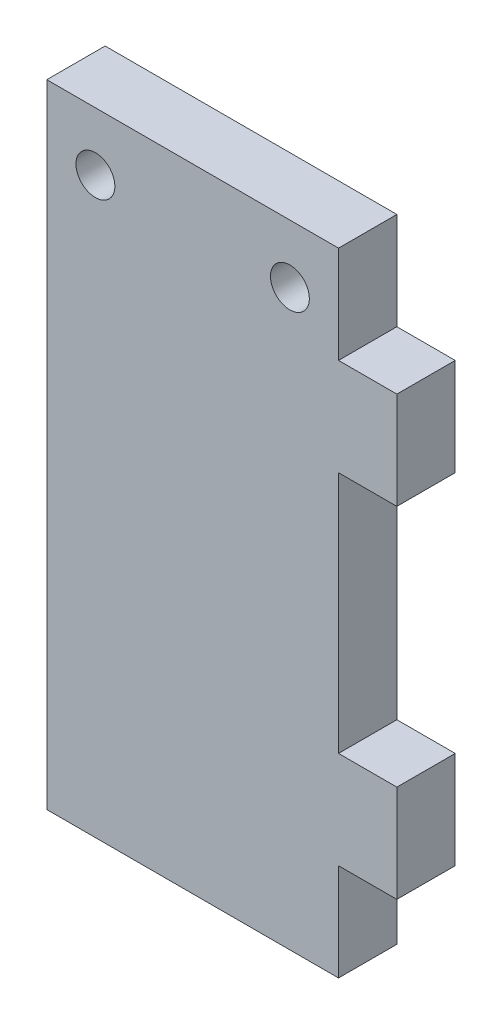
SolidWorks part; units mm, degrees
ref_plane "Plan de face" through (0, 0, 0) normal (0, 0, 1) x (1, 0, 0)
ref_plane "Plan de dessus" through (0, 0, 0) normal (0, 1, 0) x (1, 0, 0)
ref_plane "Plan de droite" through (0, 0, 0) normal (1, 0, 0) x (0, 0, -1)
sketch "Esquisse1" plane through (0, 0, 0) normal (0, 0, 1) x (1, 0, 0)
  line L1 (0, 0) -> (-30, 0)
  line L2 (0, 0) -> (0, 65)
  line L3 (0, 65) -> (-30, 65)
  line L4 (-30, 0) -> (-30, 65)
  dimension "D1" = 65
  dimension "D2" = 30
extrude "Boss.-Extru.1" add sketch "Esquisse1" along normal blind 6
sketch "Esquisse2" plane through (0, 0, 0) normal (1, 0, 0) x (0, 0, -1)
  line L0 (-6, 0) -> (-6, 65) construction
  line L1 (-6, 20) -> (0, 20)
  line L2 (-6, 20) -> (-6, 10)
  line L3 (-6, 10) -> (0, 10)
  line L4 (0, 20) -> (0, 10)
  line L5 (0, 0) -> (0, 65) construction
  line L6 (-6, 0) -> (0, 0) construction
  line L7 (-6, 65) -> (0, 65) construction
  line L8 (-6, 55) -> (0, 55)
  line L9 (-6, 55) -> (-6, 45)
  line L10 (-6, 45) -> (0, 45)
  line L11 (0, 55) -> (0, 45)
  point P14 (-3, 65)
  dimension "D1" = 10
  dimension "D2" = 10
  dimension "D3" = 10
  dimension "D4" = 10
extrude "Boss.-Extru.3" add sketch "Esquisse2" along normal blind 6
sketch "Esquisse3" plane through (0, 0, 6) normal (0, 0, 1) x (1, 0, 0)
  line L0 (-30, 65) -> (-30, 0) construction
  line L1 (0, 65) -> (-30, 65) construction
  circle A0 centre (-25, 59) radius 2
  circle A1 centre (-5, 59) radius 2
  dimension "D1" = 20
  dimension "D2" = 5
  dimension "D3" = 6
  dimension "D4" = 0
extrude "Enlèv. mat.-Extru.1" cut sketch "Esquisse3" against normal blind 6
